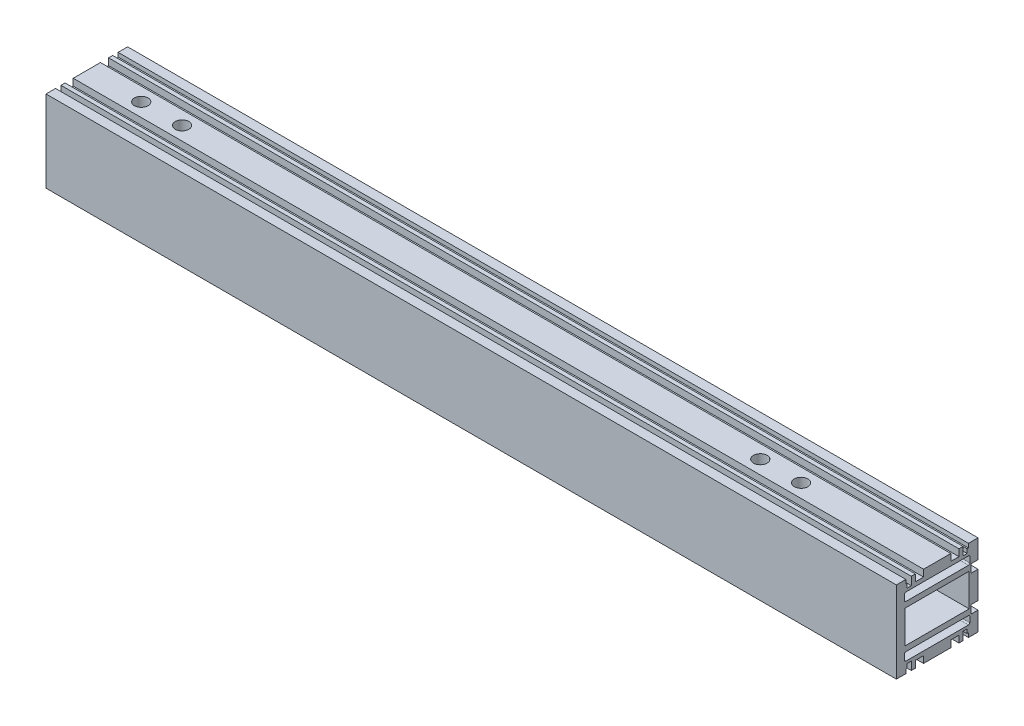
SolidWorks part; units mm, degrees
ref_plane "前视基准面" through (0, 0, 0) normal (0, 0, 1) x (1, 0, 0)
ref_plane "上视基准面" through (0, 0, 0) normal (0, 1, 0) x (1, 0, 0)
ref_plane "右视基准面" through (0, 0, 0) normal (1, 0, 0) x (0, 0, -1)
sketch "草图1" plane through (0, 0, 0) normal (1, 0, 0) x (0, 0, -1)
  line L0 (-15, 15) -> (15, -15) construction
  line L1 (-15, 15) -> (-11.5, 15)
  line L2 (-15, 15) -> (-15, -15)
  line L3 (-15, -15) -> (-11.5, -15)
  line L4 (15, 15) -> (15, 8)
  line L5 (15, 15) -> (-15, -15) construction
  line L6 (-11.5, 15) -> (-11.5, 13.5)
  line L7 (-11.5, 13.5) -> (-11, 13.5)
  line L8 (-11, 13.5) -> (-11, 12)
  line L9 (-11, 12) -> (-9.5, 12)
  line L10 (-9.5, 12) -> (-9.5, 15)
  line L11 (-9.5, 15) -> (-8, 15)
  line L12 (-8, 15) -> (-8, 12.5)
  line L13 (-8, 12.5) -> (-5, 12.5)
  line L14 (-5, 12.5) -> (-5, 15)
  line L15 (-5, 15) -> (5, 15)
  line L16 (0, 21.5201) -> (0, -18.309) construction
  line L17 (0, 55) -> (0, -55) construction
  line L18 (5, 12.5) -> (5, 15)
  line L19 (8, 12.5) -> (5, 12.5)
  line L20 (8, 15) -> (8, 12.5)
  line L21 (9.5, 15) -> (8, 15)
  line L22 (9.5, 12) -> (9.5, 15)
  line L23 (11, 12) -> (9.5, 12)
  line L24 (11, 13.5) -> (11, 12)
  line L25 (11.5, 13.5) -> (11, 13.5)
  line L26 (11.5, 15) -> (11.5, 13.5)
  line L27 (8, 15) -> (9.5, 15)
  line L28 (11.5, 15) -> (15, 15)
  line L29 (-19.8303, 0) -> (22.13, 0) construction
  line L30 (55, 0) -> (-55, 0) construction
  line L31 (8, -15) -> (9.5, -15)
  line L32 (11.5, -15) -> (11.5, -13.5)
  line L33 (11.5, -13.5) -> (11, -13.5)
  line L34 (11, -13.5) -> (11, -12)
  line L35 (11, -12) -> (9.5, -12)
  line L36 (9.5, -12) -> (9.5, -15)
  line L37 (9.5, -15) -> (8, -15)
  line L38 (8, -15) -> (8, -12.5)
  line L39 (8, -12.5) -> (5, -12.5)
  line L40 (5, -12.5) -> (5, -15)
  line L41 (-5, -15) -> (5, -15)
  line L42 (-5, -12.5) -> (-5, -15)
  line L43 (-8, -12.5) -> (-5, -12.5)
  line L44 (-8, -15) -> (-8, -12.5)
  line L45 (-9.5, -15) -> (-8, -15)
  line L46 (-9.5, -12) -> (-9.5, -15)
  line L47 (-11, -12) -> (-9.5, -12)
  line L48 (-11, -13.5) -> (-11, -12)
  line L49 (-11.5, -13.5) -> (-11, -13.5)
  line L50 (-11.5, -15) -> (-11.5, -13.5)
  line L51 (-9.5, -15) -> (-8, -15)
  line L52 (-5, -15) -> (5, -15)
  line L53 (8, -15) -> (9.5, -15)
  line L54 (11.5, -15) -> (15, -15)
  line L55 (15, 8) -> (12.5, 8)
  line L56 (12.5, 8) -> (12.5, 5)
  line L57 (12.5, 5) -> (15, 5)
  line L58 (12.5, -5) -> (15, -5)
  line L59 (12.5, -8) -> (12.5, -5)
  line L60 (15, -8) -> (12.5, -8)
  line L61 (15, 5) -> (15, -5)
  line L62 (15, -8) -> (15, -15)
  line L63 (12, -10.5) -> (12, -8.5)
  line L64 (-11.5, 11) -> (11.5, 11)
  line L65 (-12, 10.5) -> (-12, 8.5)
  line L66 (-11.5, 8) -> (11.5, 8)
  line L67 (12, 10.5) -> (12, 8.5)
  line L68 (-11.5, -8) -> (11.5, -8)
  line L69 (-12, -10.5) -> (-12, -8.5)
  line L70 (-11.5, -11) -> (11.5, -11)
  line L72 (-11.75, 6) -> (11.75, 6)
  line L73 (-11.75, 6) -> (-11.75, -6)
  line L74 (-11.75, -6) -> (11.75, -6)
  line L75 (11.75, 6) -> (11.75, -6)
  arc A0 (12, 8.5) -> (11.5, 8) centre (11.5, 8.5) cw
  arc A1 (11.5, 11) -> (12, 10.5) centre (11.5, 10.5) cw
  arc A2 (-11.5, 11) -> (-12, 10.5) centre (-11.5, 10.5) ccw
  arc A3 (-11.5, 8) -> (-12, 8.5) centre (-11.5, 8.5) cw
  arc A8 (-11.5, -8) -> (-12, -8.5) centre (-11.5, -8.5) ccw
  arc A9 (-11.5, -11) -> (-12, -10.5) centre (-11.5, -10.5) cw
  arc A10 (11.5, -11) -> (12, -10.5) centre (11.5, -10.5) ccw
  arc A11 (12, -8.5) -> (11.5, -8) centre (11.5, -8.5) ccw
  point P69 (12, 11)
  point P72 (-12, 11)
  point P77 (-11, -13.5)
  point P80 (11, -13.5)
  point P83 (11, 13.5)
  point P86 (-11, 13.5)
  point P99 (-12, -11)
  point P100 (12, -11)
  dimension "D17" = 0.5
  dimension "D1" = 3.5
  dimension "D2" = 1.5
  dimension "D3" = 0.5
  dimension "D4" = 1.5
  dimension "D5" = 3
  dimension "D6" = 30
  dimension "D7" = 30
  dimension "D8" = 1.5
  dimension "D9" = 2.5
  dimension "D10" = 3
  dimension "D11" = 2.5
  dimension "D12" = 7
  dimension "D13" = 3
  dimension "D14" = 4
  dimension "D15" = 3
  dimension "D16" = 24
  dimension "D19" = 23.5
  dimension "D20" = 12
extrude "凸台-拉伸1" add sketch "草图1" along normal mid plane 312.5
hole_wizard "M6 螺纹孔1" positions "草图3" profile "草图2" tap size "M6" standard "GB"
sketch "草图3" plane through (0, 15, 0) normal (0, 1, 0) x (1, 0, 0)
  point P0 (106.25, 0)
  point P3 (91.25, 0)
  point P6 (-121.25, 0)
  point P9 (-136.25, 0)
sketch "草图2" plane through (106.25, 15, 0) normal (1, 0, 0) x (0, 0, 1)
  line L0 (0, 0) -> (0, 20.5022)
  line L1 (0, 20.5022) -> (2.5, 19)
  line L2 (2.5, 19) -> (2.5, 0)
  line L5 (2.5, 0) -> (0, 0)
  line L10 (0, 20.5022) -> (-2.5, 19) construction
  line L11 (0, -6.35) -> (0, 107.95) construction
  dimension "螺纹孔钻头直径" = 5
  dimension "螺纹孔钻头深度" = 19
  dimension "导头角度" = 118
cosmetic thread "孔螺蚊线1" parameters "D1"=9, "D2"=6
cosmetic thread "孔螺蚊线2" parameters "D1"=9, "D2"=6
cosmetic thread "孔螺蚊线3" parameters "D1"=9, "D2"=6
cosmetic thread "孔螺蚊线4" parameters "D1"=9, "D2"=6
